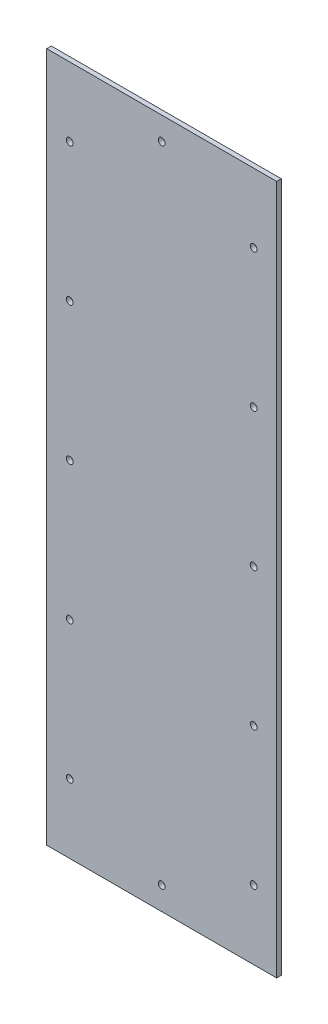
SolidWorks part; units mm, degrees
ref_plane "Front Plane" through (0, 0, 0) normal (0, 0, 1) x (1, 0, 0)
ref_plane "Top Plane" through (0, 0, 0) normal (0, 1, 0) x (1, 0, 0)
ref_plane "Right Plane" through (0, 0, 0) normal (1, 0, 0) x (0, 0, -1)
sketch "Sketch1" plane through (0, 0, 0) normal (0, 0, 1) x (1, 0, 0)
  line L1 (0, 0) -> (100, 0)
  line L2 (0, 0) -> (0, -300)
  line L3 (0, -300) -> (100, -300)
  line L4 (100, 0) -> (100, -300)
  dimension "D1" = 100
  dimension "D2" = 300
extrude "Boss-Extrude1" add sketch "Sketch1" along normal blind 2
sketch "Sketch3" plane through (0, 0, 2) normal (0, 0, 1) x (1, 0, 0)
  line L0 (10, 0) -> (10, -300) construction
  line L1 (100, 0) -> (0, 0) construction
  line L2 (0, -300) -> (100, -300) construction
  line L3 (0, 0) -> (0, -300) construction
  line L4 (100, -150) -> (0, -150) construction
  line L5 (100, -300) -> (100, 0) construction
  line L6 (100, -30) -> (0, -30)
  line L7 (100, -270) -> (0, -270)
  line L8 (100, -90) -> (0, -90) construction
  line L9 (100, -210) -> (0, -210) construction
  line L10 (50, 0) -> (50, -300) construction
  line L11 (100, -10) -> (0, -10) construction
  circle A0 centre (10, -30) radius 1.5
  circle A1 centre (10, -90) radius 1.5
  circle A2 centre (10, -150) radius 1.5
  circle A3 centre (10, -210) radius 1.5
  circle A4 centre (10, -270) radius 1.5
  circle A5 centre (90, -150) radius 1.5
  circle A6 centre (90, -90) radius 1.5
  circle A7 centre (90, -30) radius 1.5
  circle A8 centre (90, -270) radius 1.5
  circle A9 centre (90, -210) radius 1.5
  circle A10 centre (50, -10) radius 1.5
  circle A11 centre (50, -290) radius 1.5
  dimension "D4" = 3
  dimension "D1" = 10
  dimension "D2" = 30
  dimension "D3" = 60
  dimension "D5" = 10
extrude "Cut-Extrude1" cut sketch "Sketch3" against normal through all contours A10 | A0 | A1 | A2 | A3 | A4 | A11 | A8 | A9 | A5 | A6 | A7
equation "\"a\"=10"
